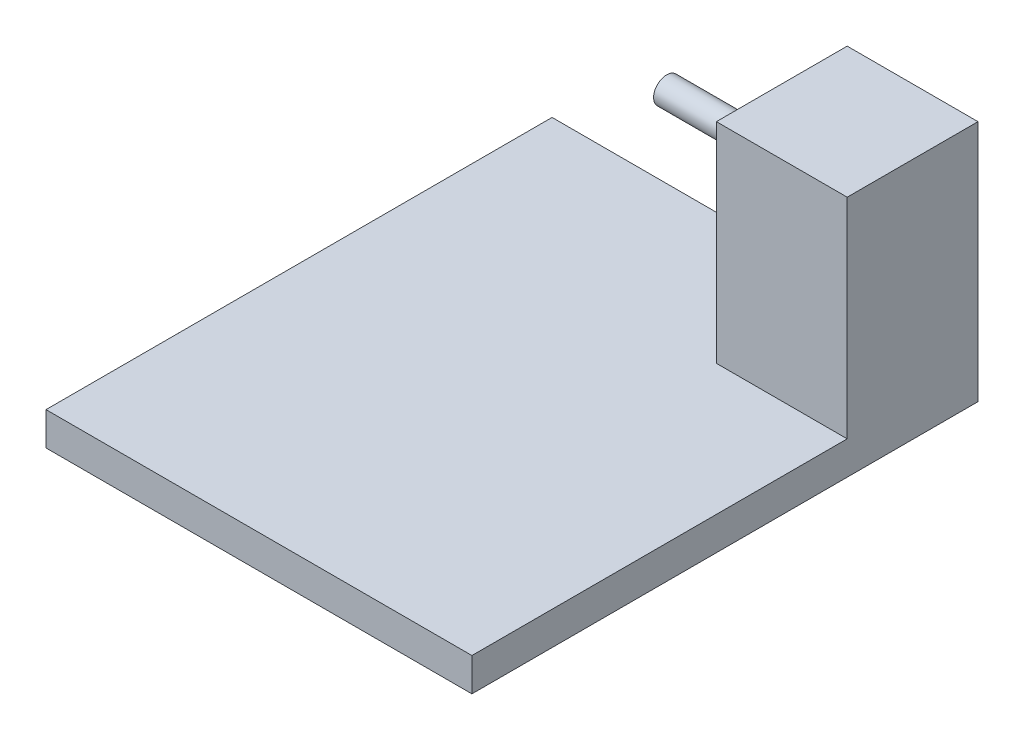
SolidWorks part; units mm, degrees
ref_plane "Front Plane" through (0, 0, 0) normal (0, 0, 1) x (1, 0, 0)
ref_plane "Top Plane" through (0, 0, 0) normal (0, 1, 0) x (1, 0, 0)
ref_plane "Right Plane" through (0, 0, 0) normal (1, 0, 0) x (0, 0, -1)
sketch "Sketch1" plane through (0, 0, 0) normal (0, 1, 0) x (1, 0, 0)
  line L1 (-40.7, 48.36) -> (40.7, 48.36)
  line L2 (-40.7, 48.36) -> (-40.7, -48.36)
  line L3 (-40.7, -48.36) -> (40.7, -48.36)
  line L4 (40.7, 48.36) -> (40.7, -48.36)
  line L5 (-40.7, 48.36) -> (40.7, -48.36) construction
  line L6 (-40.7, -48.36) -> (40.7, 48.36) construction
  point P0 (0, 0)
  dimension "D1" = 81.4
  dimension "D2" = 96.72
extrude "Boss-Extrude1" add sketch "Sketch1" along normal blind 6.35
sketch "Sketch2" plane through (0, 6.35, 0) normal (0, 1, 0) x (1, 0, 0)
  line L5 (40.7, 48.36) -> (40.7, 23.36)
  line L6 (40.7, 48.36) -> (15.7, 48.36)
  line L7 (40.7, 23.36) -> (15.7, 23.36)
  line L8 (15.7, 48.36) -> (15.7, 23.36)
  line L9 (40.7, -48.36) -> (40.7, 48.36) construction
  dimension "D1" = 25
  dimension "D2" = 25
extrude "Boss-Extrude2" add sketch "Sketch2" along normal blind 40
sketch "Sketch3" plane through (15.7, 0, 0) normal (-1, 0, 0) x (0, 0, 1)
  line L0 (-35.86, 6.35) -> (-35.86, 46.35) construction
  line L1 (-48.36, 6.35) -> (-23.36, 6.35) construction
  line L2 (-48.36, 46.35) -> (-23.36, 46.35) construction
  circle A0 centre (-35.86, 34.35) radius 2.5
  dimension "D1" = 5
  dimension "D2" = 28
extrude "Boss-Extrude3" add sketch "Sketch3" along normal blind 22
